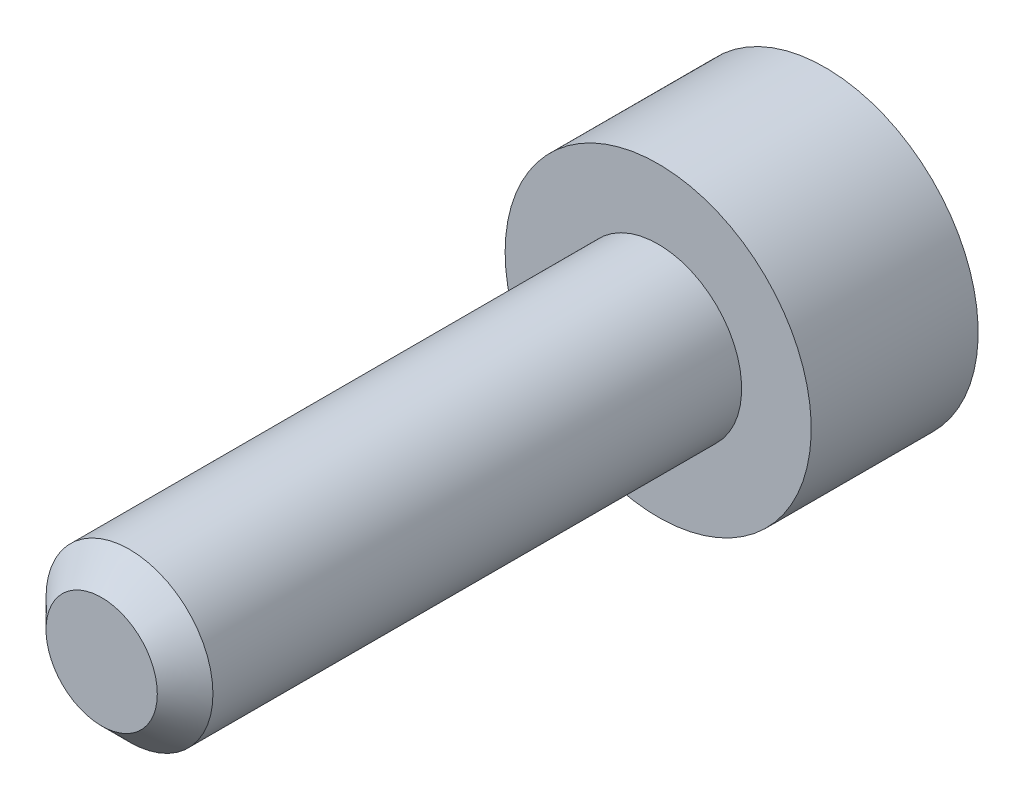
SolidWorks part; units mm, degrees
material "Alliage 1060"
ref_plane "Plan de face" through (0, 0, 0) normal (0, 0, 1) x (1, 0, 0)
ref_plane "Plan de dessus" through (0, 0, 0) normal (0, 1, 0) x (1, 0, 0)
ref_plane "Plan de droite" through (0, 0, 0) normal (1, 0, 0) x (0, 0, -1)
sketch "Esquisse2" plane through (0, 0, 0) normal (0, 0, 1) x (1, 0, 0)
  circle A0 centre (0, 0) radius 1.5
  dimension "D1" = 3
extrude "Extrusion1" add sketch "Esquisse2" along normal blind 10
sketch "Esquisse3" plane through (0, 0, 0) normal (0, 0, -1) x (-1, 0, 0)
  circle A0 centre (0, 0) radius 2.75
  dimension "D1" = 5.5
extrude "Extrusion2" add sketch "Esquisse3" along normal blind 3
chamfer "Chanfrein1" distance 0.5 angle 45 1 edges at (1.5, 0, 10)
